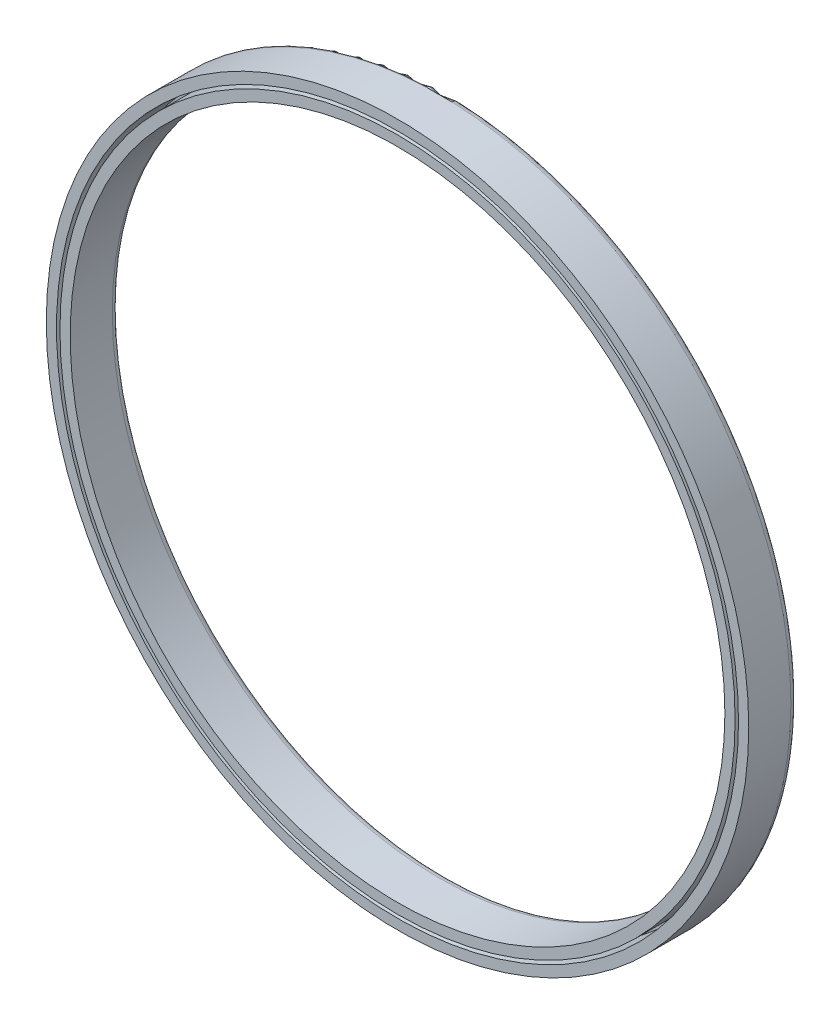
SolidWorks part; units mm, degrees
ref_plane "Front Plane" through (0, 0, 0) normal (0, 0, 1) x (1, 0, 0)
ref_plane "Top Plane" through (0, 0, 0) normal (0, 1, 0) x (1, 0, 0)
ref_plane "Right Plane" through (0, 0, 0) normal (1, 0, 0) x (0, 0, -1)
sketch "Sketch1" plane through (0, 0, 0) normal (0, 1, 0) x (1, 0, 0)
  line L0 (0, 0) -> (-99, 0) construction
  line L1 (-99, 0) -> (-99, 11.3556)
  line L2 (-99, 11.3556) -> (-100, 11.3556)
  line L3 (-100, 11.3556) -> (-100, 0)
  line L4 (-100, 0) -> (-103, 0)
  line L5 (-103, 0) -> (-103, 14.3556)
  line L6 (-103, 14.3556) -> (-96, 14.3556)
  line L7 (-96, 14.3556) -> (-96, 0)
  line L8 (-96, 0) -> (-99, 0)
  line L9 (0, 0) -> (0, 18.8685) construction
  dimension "D1" = 99
  dimension "D2" = 1
  dimension "D3" = 3
  dimension "D4" = 3
revolve "Revolve1" add sketch "Sketch1" angle 360 about L9
fillet "Fillet2" radius 2 1 edges at (103, 0, -14.3556)
fillet "Fillet3" radius 2 1 edges at (96, 0, -14.3556)
